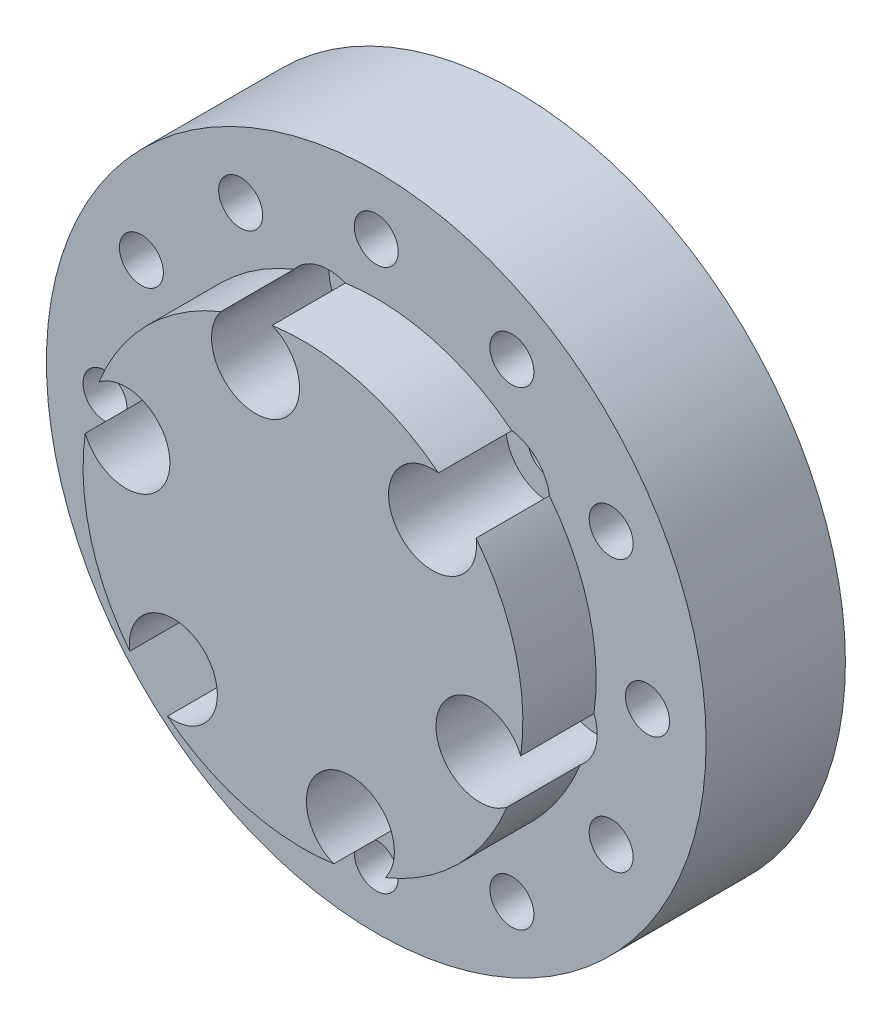
SolidWorks part; units mm, degrees
ref_plane "前视基准面" through (0, 0, 0) normal (0, 0, 1) x (1, 0, 0)
ref_plane "上视基准面" through (0, 0, 0) normal (0, 1, 0) x (1, 0, 0)
ref_plane "右视基准面" through (0, 0, 0) normal (1, 0, 0) x (0, 0, -1)
other "Configuration Table"
sketch "草图1" plane through (0, 0, 0) normal (0, 0, 1) x (1, 0, 0)
  circle A0 centre (0, 0) radius 22.5
  dimension "D1" = 45
extrude "凸台-拉伸1" add sketch "草图1" along normal blind 9.5
sketch "草图2" plane through (0, 0, 9.5) normal (0, 0, 1) x (1, 0, 0)
  circle A0 centre (0, 0) radius 15
  dimension "D1" = 30
extrude "凸台-拉伸2" add sketch "草图2" along normal blind 5
sketch "草图3" plane through (0, 0, 9.5) normal (0, 0, 1) x (1, 0, 0)
  circle A0 centre (0, 0) radius 18.5 construction
  circle A1 centre (0, 18.5) radius 1.5
  dimension "D1" = 37
  dimension "D2" = 3
extrude "切除-拉伸1" cut sketch "草图3" against normal blind 5
sketch "草图5" plane through (0, 0, 9.5) normal (0, 0, 1) x (1, 0, 0)
  circle A0 centre (0, 18.5) radius 1.5
  dimension "D1" = 3
extrude "切除-拉伸2" cut sketch "草图5" against normal through all
sketch "草图9" plane through (0, 0, 0) normal (0, 0, -1) x (-1, 0, 0)
  line L1 (1.2045, 21.4381) -> (-1.9422, 21.0122)
  line L2 (-1.9422, 21.0122) -> (-3.1467, 18.0741)
  line L3 (-3.1467, 18.0741) -> (-1.2045, 15.5619)
  line L4 (-1.2045, 15.5619) -> (1.9422, 15.9878)
  line L5 (1.9422, 15.9878) -> (3.1467, 18.9259)
  line L6 (3.1467, 18.9259) -> (1.2045, 21.4381)
  circle A0 centre (0, 18.5) radius 2.75 construction
  dimension "D1" = 5.5
extrude "切除-拉伸6" cut sketch "草图9" against normal blind 3
pattern_circular "阵列(圆周)1" count 12 over 360 about axis through (0, 0, 0) along (0, 0, 1) of "切除-拉伸1", "切除-拉伸6", "切除-拉伸2"
sketch "草图6" plane through (0, 0, 0) normal (0, 0, -1) x (-1, 0, 0)
  line L0 (0, 18.5) -> (9.25, 16.0215) construction
  line L1 (4.625, 17.2607) -> (0, 0) construction
  circle A0 centre (0, 0) radius 12.5 construction
  circle A1 centre (3.2352, 12.0741) radius 1.5
  dimension "D1" = 3
  dimension "D2" = 25
sketch "草图7" plane through (0, 0, 14.5) normal (0, 0, 1) x (1, 0, 0)
  circle A0 centre (-3.2352, 12.0741) radius 3
  dimension "D1" = 6
extrude "切除-拉伸3" cut sketch "草图6" against normal through all contours A1
extrude "切除-拉伸4" cut sketch "草图7" against normal offset from surface (8 mm away) 3 contours A0 up to face at (-15.2715, 10.549, 9.5) offset beyond the face yes
pattern_circular "阵列(圆周)2" count 6 over 360 about axis through (0, 0, 0) along (0, 0, 1) of "切除-拉伸3", "切除-拉伸4"
sketch "草图8" plane through (0, 0, 0) normal (0, 0, -1) x (-1, 0, 0)
  line L0 (0, 0) -> (-12940.9523, 48296.2913) construction
  line L1 (3.2352, 12.0741) -> (-8.8388, 8.8388) construction
  line L2 (-8.8388, 8.8388) -> (-12.0741, -3.2352) construction
  line L3 (-12.0741, -3.2352) -> (-3.2352, -12.0741) construction
  line L4 (-3.2352, -12.0741) -> (8.8388, -8.8388) construction
  line L5 (8.8388, -8.8388) -> (12.0741, 3.2352) construction
  line L6 (12.0741, 3.2352) -> (3.2352, 12.0741) construction
  circle A0 centre (0, 0) radius 10.8253 construction
  circle A1 centre (-2.64, 9.8524) radius 2
  circle A2 centre (0, 0) radius 10.2 construction
  point P13 (-2.8018, 10.4565)
  dimension "D1" = 4
  dimension "D2" = 20.4
extrude "切除-拉伸5" cut sketch "草图8" against normal blind 4
pattern_circular "阵列(圆周)3" count 6 every 60 about axis through (0, 0, 0) along (0, 0, 1) of "切除-拉伸5"
